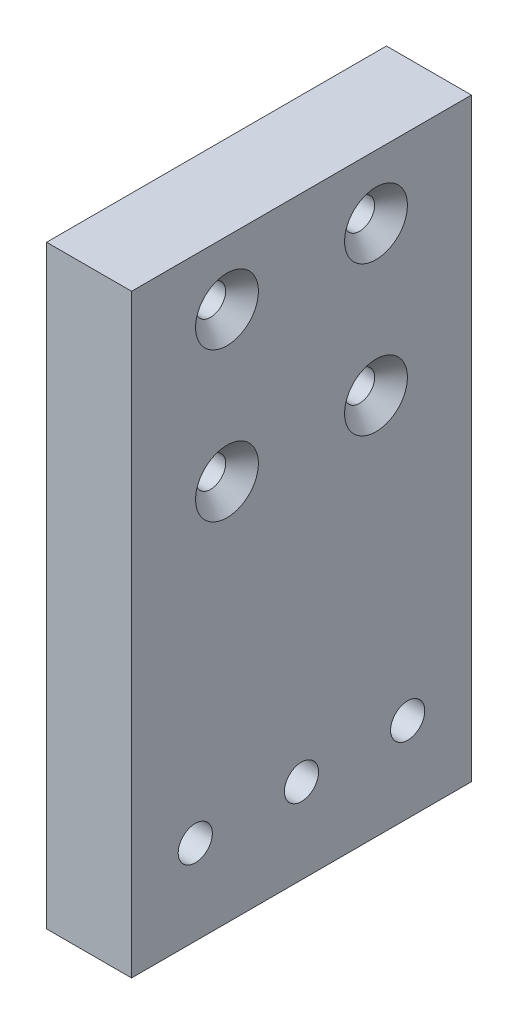
SolidWorks part; units mm, degrees
material "Nylon 6/10"
ref_plane "Front Plane" through (0, 0, 0) normal (0, 0, 1) x (1, 0, 0)
ref_plane "Top Plane" through (0, 0, 0) normal (0, 1, 0) x (1, 0, 0)
ref_plane "Right Plane" through (0, 0, 0) normal (1, 0, 0) x (0, 0, -1)
sketch "Sketch1" plane through (0, 0, 0) normal (1, 0, 0) x (0, 0, -1)
  line L1 (-25.4, -44.45) -> (25.4, -44.45)
  line L2 (-25.4, -44.45) -> (-25.4, 44.45)
  line L3 (-25.4, 44.45) -> (25.4, 44.45)
  line L4 (25.4, -44.45) -> (25.4, 44.45)
  line L5 (-25.4, -44.45) -> (25.4, 44.45) construction
  line L6 (-25.4, 44.45) -> (25.4, -44.45) construction
  point P0 (0, 0)
  dimension "D1" = 50.8
  dimension "D2" = 88.9
extrude "Boss-Extrude1" add sketch "Sketch1" along normal blind 12.7
hole_wizard "CSK for M4 Flat Head Machine Screw1" positions "Sketch3" profile "Sketch2" countersink size "M4" standard "ANSI Metric" end condition through all
sketch "Sketch3" plane through (12.7, 0, 0) normal (1, 0, 0) x (0, 0, -1)
  line L1 (-11.1369, 12.7) -> (11.1369, 12.7) construction
  line L2 (-11.1369, 12.7) -> (-11.1369, 34.9739) construction
  line L3 (-11.1369, 34.9739) -> (11.1369, 34.9739) construction
  line L4 (11.1369, 12.7) -> (11.1369, 34.9739) construction
  line L5 (-11.1369, 12.7) -> (11.1369, 34.9739) construction
  line L6 (-11.1369, 34.9739) -> (11.1369, 12.7) construction
  line L8 (25.4, 44.45) -> (-25.4, 44.45) construction
  point P219 (11.1369, 34.9739)
  point P223 (-11.1369, 34.9739)
  point P225 (-11.1369, 12.7)
  point P227 (11.1369, 12.7)
  dimension "D1" = 31.5
  dimension "D2" = 31.75
sketch "Sketch2" plane through (12.7, 34.9739, -11.1369) normal (0, 1, 0) x (0, 0, -1)
  line L0 (0, 0) -> (0, 12.7)
  line L1 (0, 12.7) -> (2.25, 12.7)
  line L2 (2.25, 12.7) -> (2.25, 2.45)
  line L3 (2.25, 2.45) -> (4.7, 0)
  line L5 (4.7, 0) -> (0, 0)
  line L6 (-2.25, 2.45) -> (-4.7, 0) construction
  line L11 (0, -6.35) -> (0, 107.95) construction
  dimension "Thru Hole Dia." = 4.5
  dimension "Thru Hole Depth" = 12.7
  dimension "Near C'Sink Dia." = 9.4
  dimension "Near C'Sink Angle" = 90
hole_wizard "CBORE for #10 Socket Head Cap Screw1" positions "Sketch5" profile "Sketch4" counterbore size "#10" standard "ANSI Inch" end condition through all
sketch "Sketch5" plane through (0, 0, 0) normal (-1, 0, 0) x (0, 0, 1)
  line L0 (-25.4, -31.75) -> (25.4, -31.75) construction
  line L1 (-25.4, -44.45) -> (-25.4, 44.45) construction
  line L2 (25.4, 44.45) -> (25.4, -44.45) construction
  line L4 (25.4, -44.45) -> (-25.4, -44.45) construction
  line L5 (0, -44.45) -> (0, 0) construction
  point P0 (-15.875, -31.75)
  point P2 (0, -31.75)
  point P4 (15.875, -31.75)
  dimension "D1" = 12.7
  dimension "D2" = 9.525
  dimension "D3" = 9.525
sketch "Sketch4" plane through (0, -31.75, -15.875) normal (0, 1, 0) x (0, 0, 1)
  line L0 (0, 0) -> (0, 12.7)
  line L1 (0, 12.7) -> (2.5527, 12.7)
  line L3 (2.5527, 12.7) -> (2.5527, 4.826)
  line L4 (2.5527, 4.826) -> (4.7625, 4.826)
  line L5 (4.7625, 4.826) -> (4.7625, 0)
  line L7 (4.7625, 0) -> (0, 0)
  line L11 (0, -6.35) -> (0, 107.95) construction
  dimension "Thru Hole Dia." = 5.1054
  dimension "Thru Hole Depth" = 12.7
  dimension "C'Bore Dia." = 9.525
  dimension "C'Bore Depth" = 4.826
